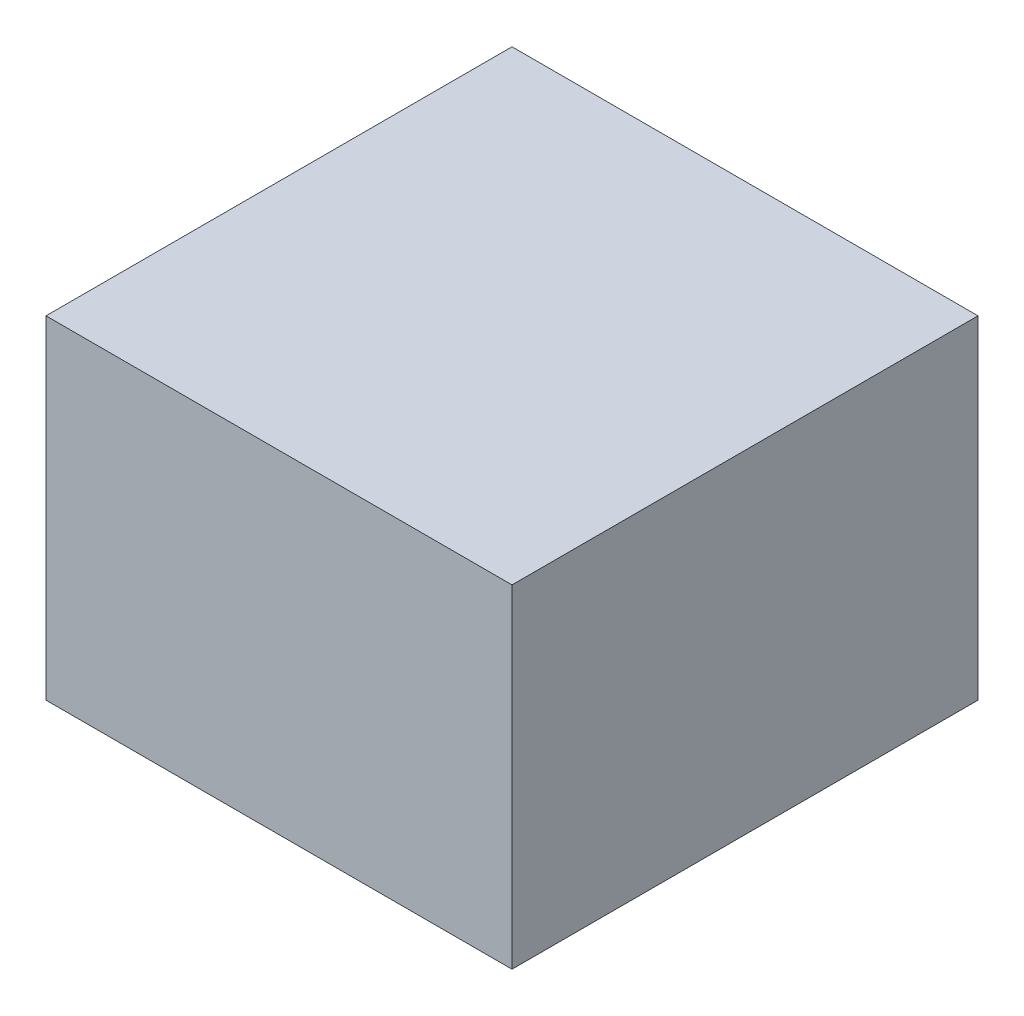
SolidWorks part; units mm, degrees
ref_plane "Front Plane" through (0, 0, 0) normal (0, 0, 1) x (1, 0, 0)
ref_plane "Top Plane" through (0, 0, 0) normal (0, 1, 0) x (1, 0, 0)
ref_plane "Right Plane" through (0, 0, 0) normal (1, 0, 0) x (0, 0, -1)
sketch "Sketch1" plane through (0, 0, 0) normal (0, 1, 0) x (1, 0, 0)
  line L1 (-350, 350) -> (350, 350)
  line L2 (-350, 350) -> (-350, -350)
  line L3 (-350, -350) -> (350, -350)
  line L4 (350, 350) -> (350, -350)
  line L5 (-350, 350) -> (350, -350) construction
  line L6 (-350, -350) -> (350, 350) construction
  point P0 (0, 0)
extrude "Boss-Extrude1" add sketch "Sketch1" along normal mid plane 500
